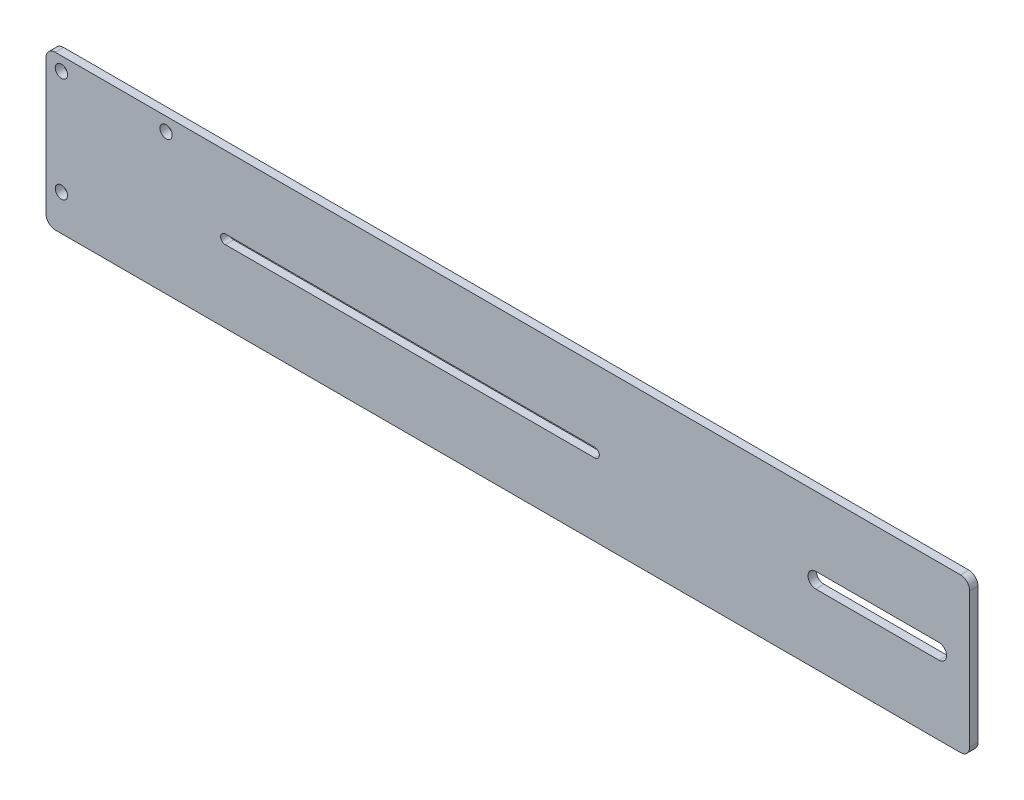
SolidWorks part; units mm, degrees
ref_plane "前视基准面" through (0, 0, 0) normal (0, 0, 1) x (1, 0, 0)
ref_plane "上视基准面" through (0, 0, 0) normal (0, 1, 0) x (1, 0, 0)
ref_plane "右视基准面" through (0, 0, 0) normal (1, 0, 0) x (0, 0, -1)
sketch "草图1" plane through (0, 0, 0) normal (0, 0, 1) x (1, 0, 0)
  line L0 (0, 22) -> (0, -22)
  line L1 (3, 25) -> (297, 25)
  line L3 (3, -25) -> (297, -25)
  line L4 (300, 22) -> (300, -22)
  line L9 (250, 2.5) -> (290, 2.5)
  line L10 (290, -2.5) -> (250, -2.5)
  line L11 (58.2194, 1.5) -> (178.2194, 1.5)
  line L15 (0, 0) -> (250, 0) construction
  line L16 (178.2194, -1.5) -> (58.2194, -1.5)
  arc A0 (300, -22) -> (297, -25) centre (297, -22) cw
  arc A1 (300, 22) -> (297, 25) centre (297, 22) ccw
  arc A2 (0, -22) -> (3, -25) centre (3, -22) ccw
  arc A3 (0, 22) -> (3, 25) centre (3, 22) cw
  circle A8 centre (5, 20.65) radius 2
  circle A9 centre (39, 20.65) radius 2
  circle A10 centre (5, -13.35) radius 2
  arc A11 (250, 2.5) -> (250, -2.5) centre (250, 0) ccw
  arc A12 (290, -2.5) -> (290, 2.5) centre (290, 0) ccw
  arc A17 (58.2194, 1.5) -> (58.2194, -1.5) centre (58.2194, 0) ccw
  arc A18 (178.2194, -1.5) -> (178.2194, 1.5) centre (178.2194, 0) ccw
  dimension "D1" = 3
  dimension "D2" = 5
  dimension "D4" = 10
  dimension "D7" = 120
  dimension "D5" = 40
  dimension "D6" = 300
extrude "凸台-拉伸1" add sketch "草图1" along normal blind 2.7 contours A3 L0 A2 L3 A0 L4 A1 L1 A12 L10 A11 L9 A10 A9 A8
